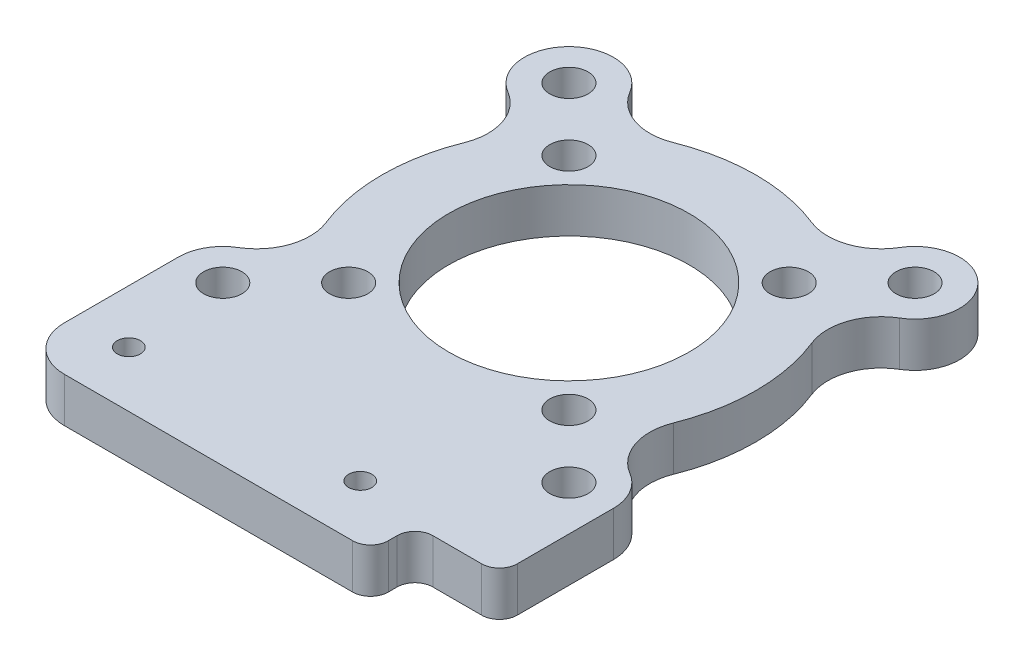
SolidWorks part; units mm, degrees
material "5052-H34"
ref_plane "正面" through (0, 0, 0) normal (0, 0, 1) x (1, 0, 0)
ref_plane "平面" through (0, 0, 0) normal (0, 1, 0) x (1, 0, 0)
ref_plane "右側面" through (0, 0, 0) normal (1, 0, 0) x (0, 0, -1)
sketch "ｽｹｯﾁ1" plane through (0, 0, 0) normal (0, 1, 0) x (1, 0, 0)
  line L0 (19.4454, 19.4454) -> (0, 0) construction
  line L3 (0, 0) -> (0, -31) construction
  line L4 (0, 0) -> (13.5, 0) construction
  line L5 (0, 0) -> (12.3744, 12.3744) construction
  line L6 (7.5546, -31) -> (-18.4454, -31) construction
  line L7 (-24.4454, -32.25) -> (-24.4454, -19.4454)
  line L10 (-19.4454, -37.25) -> (14.9532, -37.25)
  line L12 (19.4454, -19.4454) -> (19.4454, -39.4454) construction
  line L15 (24.4454, -32.25) -> (24.4454, -19.4454)
  line L16 (14.9532, -37.25) -> (14.9532, -32.25)
  line L17 (14.9532, -32.25) -> (24.4454, -32.25)
  line L18 (14.9532, -37.25) -> (19.4454, -37.25) construction
  circle A4 centre (0, 0) radius 13.5
  circle A5 centre (12.3744, 12.3744) radius 2.15
  circle A6 centre (12.3744, -12.3744) radius 2.15
  circle A7 centre (-12.3744, -12.3744) radius 2.15
  circle A8 centre (-12.3744, 12.3744) radius 2.15
  circle A9 centre (19.4454, 19.4454) radius 2.15
  arc A13 (19.5071, -7.7766) -> (19.5071, 7.7766) centre (0, 0) ccw
  arc A14 (22.0068, 15.1513) -> (15.1513, 22.0068) centre (19.4454, 19.4454) ccw
  arc A18 (15.1513, 22.0068) -> (7.7766, 19.5071) centre (9.9984, 25.0805) cw
  arc A19 (22.0068, 15.1513) -> (19.5071, 7.7766) centre (25.0805, 9.9984) ccw
  arc A20 (24.4454, -19.4454) -> (22.0068, -15.1513) centre (19.4454, -19.4454) ccw
  arc A21 (15.1513, -22.0068) -> (7.7766, -19.5071) centre (9.9984, -25.0805) ccw construction
  circle A22 centre (19.4454, -19.4454) radius 2.15
  arc A23 (22.0068, -15.1513) -> (19.5071, -7.7766) centre (25.0805, -9.9984) cw
  arc A24 (-22.0068, -15.1513) -> (-24.4454, -19.4454) centre (-19.4454, -19.4454) ccw
  arc A25 (-22.0068, -15.1513) -> (-19.5071, -7.7766) centre (-25.0805, -9.9984) ccw
  circle A26 centre (-19.4454, -19.4454) radius 2.15
  arc A27 (-15.1513, -22.0068) -> (-7.7766, -19.5071) centre (-9.9984, -25.0805) cw construction
  arc A28 (-15.1513, 22.0068) -> (-22.0068, 15.1513) centre (-19.4454, 19.4454) ccw
  arc A29 (-15.1513, 22.0068) -> (-7.7766, 19.5071) centre (-9.9984, 25.0805) ccw
  circle A30 centre (-19.4454, 19.4454) radius 2.15
  arc A31 (-22.0068, 15.1513) -> (-19.5071, 7.7766) centre (-25.0805, 9.9984) cw
  arc A32 (0, -21) -> (7.7766, -19.5071) centre (0, 0) ccw construction
  arc A33 (7.7766, 19.5071) -> (-7.7766, 19.5071) centre (0, 0) ccw
  arc A34 (-19.5071, 7.7766) -> (-19.5071, -7.7766) centre (0, 0) ccw
  circle A35 centre (7.5546, -31) radius 1.3
  arc A37 (22.9177, -35.8477) -> (24.4454, -32.25) centre (19.4454, -32.25) ccw construction
  arc A38 (-19.4454, -37.25) -> (-24.4454, -32.25) centre (-19.4454, -32.25) cw
  arc A39 (-7.7766, -19.5071) -> (0, -21) centre (0, 0) ccw construction
  arc A40 (15.1513, -22.0068) -> (24.4454, -19.4454) centre (19.4454, -19.4454) ccw construction
  arc A41 (-24.4454, -19.4454) -> (-15.1513, -22.0068) centre (-19.4454, -19.4454) ccw construction
  circle A42 centre (-18.4454, -31) radius 1.3
  arc A43 (22.9177, -35.8477) -> (19.4454, -34.4454) centre (19.4454, -39.4454) ccw construction
  arc A44 (14.9532, -37.25) -> (22.9177, -35.8477) centre (19.4454, -39.4454) ccw construction
  arc A45 (19.4454, -34.4454) -> (14.9532, -37.25) centre (19.4454, -39.4454) ccw construction
  arc A46 (19.4454, -37.25) -> (22.9177, -35.8477) centre (19.4454, -32.25) ccw construction
  point P17 (0, 0)
  point P24 (0, 0)
  point P33 (0, 0)
  dimension "D2" = 10
  dimension "D4" = 27.5
  dimension "D5" = 2.6
  dimension "D6" = 27
  dimension "D8" = 4.3
  dimension "D3" = 4.3
  dimension "D12" = 42
  dimension "D14" = 6
  dimension "D18" = 5
  dimension "D19" = 10
  dimension "D7" = 45
  dimension "D9" = 17.5
  dimension "D11" = 45
  dimension "D13" = 26
  dimension "D15" = 6
  dimension "D16" = 6.25
  dimension "D17" = 31
  dimension "D20" = 20
  dimension "D21" = 5
  dimension "D10" = 4
extrude "ﾎﾞｽ - 押し出し1" add sketch "ｽｹｯﾁ1" along normal blind 5 contours A43 A37 L15 A20 A23 A13 A19 A14 A18 A33 A29 A28 A31 A34 A25 A24 L7 A38 L10 A42 A35 A30 A26 A22 A9 A8 A7 A6 A5 A4
fillet "ﾌｨﾚｯﾄ1" radius 2 3 edges at (14.9532, 2.5, 37.25) (14.9532, 2.5, 32.25) (24.4454, 2.5, 32.25)
